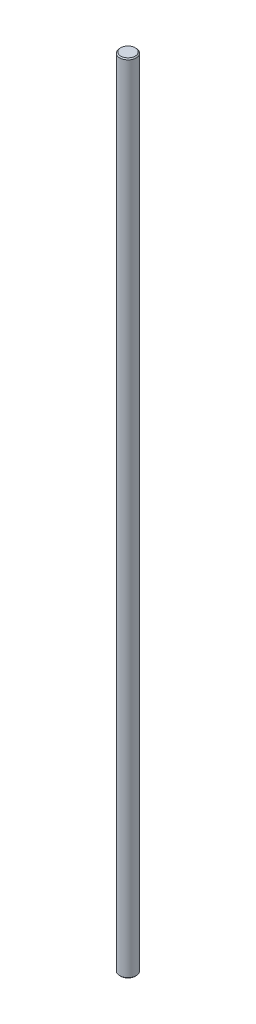
SolidWorks part; units mm, degrees
ref_plane "Front Plane" through (0, 0, 0) normal (0, 0, 1) x (1, 0, 0)
ref_plane "Top Plane" through (0, 0, 0) normal (0, 1, 0) x (1, 0, 0)
ref_plane "Right Plane" through (0, 0, 0) normal (1, 0, 0) x (0, 0, -1)
sketch "Sketch1" plane through (0, 0, 0) normal (0, 1, 0) x (1, 0, 0)
  circle A0 centre (0, 0) radius 3.95
  dimension "D1" = 7.9
extrude "Boss-Extrude1" add sketch "Sketch1" along normal blind 380
chamfer "Chamfer1" distance 0.5 angle 45 1 edges at (0, 380, 3.95)
chamfer "Chamfer2" distance 0.5 angle 45 1 edges at (0, 0, 3.95)
